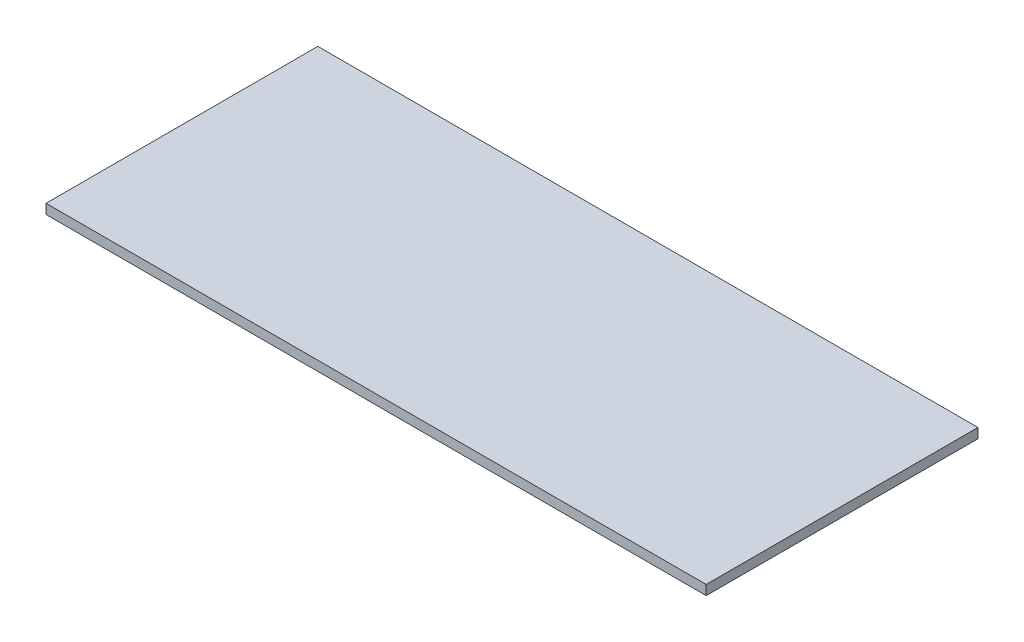
SolidWorks part; units mm, degrees
ref_plane "Alzado" through (0, 0, 0) normal (0, 0, 1) x (1, 0, 0)
ref_plane "Planta" through (0, 0, 0) normal (0, 1, 0) x (1, 0, 0)
ref_plane "Vista lateral" through (0, 0, 0) normal (1, 0, 0) x (0, 0, -1)
sketch "Croquis1" plane through (0, 0, 0) normal (0, 1, 0) x (1, 0, 0)
  line L1 (-340, -140) -> (340, -140)
  line L2 (-340, -140) -> (-340, 140)
  line L3 (-340, 140) -> (340, 140)
  line L4 (340, -140) -> (340, 140)
  line L5 (-340, -140) -> (340, 140) construction
  line L6 (-340, 140) -> (340, -140) construction
  point P0 (0, 0)
  dimension "D1" = 680
  dimension "D2" = 280
extrude "Saliente-Extruir1" add sketch "Croquis1" along normal blind 10
